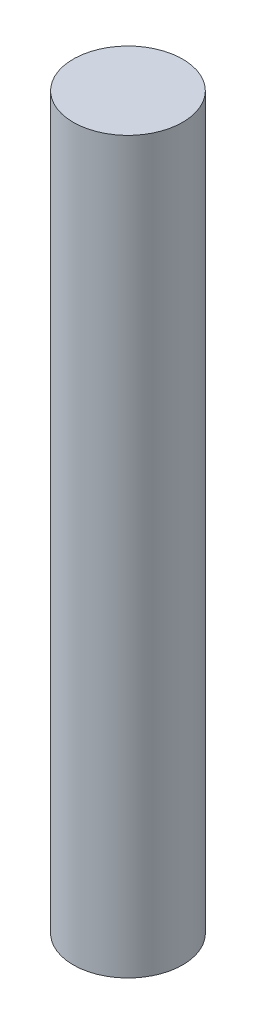
SolidWorks part; units mm, degrees
ref_plane "Front Plane" through (0, 0, 0) normal (0, 0, 1) x (1, 0, 0)
ref_plane "Top Plane" through (0, 0, 0) normal (0, 1, 0) x (1, 0, 0)
ref_plane "Right Plane" through (0, 0, 0) normal (1, 0, 0) x (0, 0, -1)
sketch "Sketch1" plane through (0, 0, 0) normal (0, 1, 0) x (1, 0, 0)
  circle A0 centre (0, 0) radius 0.75
  dimension "D1" = 1.5
extrude "Boss-Extrude1" add sketch "Sketch1" along normal blind 10 contours A0
